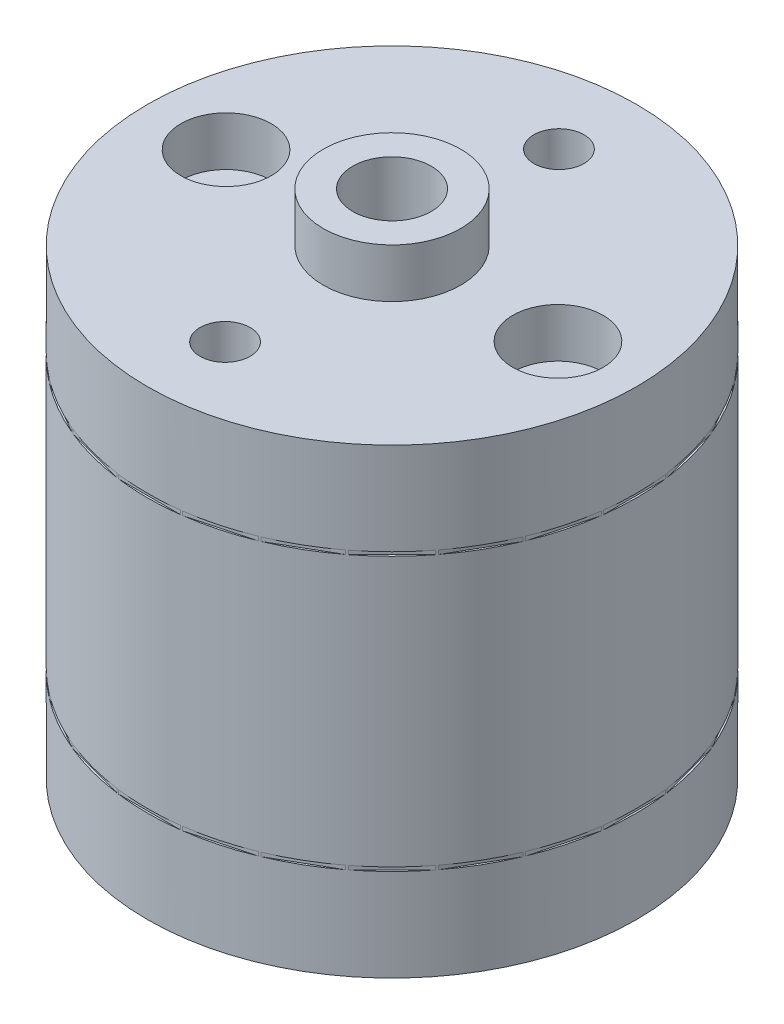
SolidWorks part; units mm, degrees
ref_plane "Alzado" through (0, 0, 0) normal (0, 0, 1) x (1, 0, 0)
ref_plane "Planta" through (0, 0, 0) normal (0, 1, 0) x (1, 0, 0)
ref_plane "Vista lateral" through (0, 0, 0) normal (1, 0, 0) x (0, 0, -1)
sketch "Croquis1" plane through (0, 0, 0) normal (0, 1, 0) x (1, 0, 0)
  circle A0 centre (0, 0) radius 12.45
  dimension "D1" = 24.9
extrude "Saliente-Extruir1" add sketch "Croquis1" along normal blind 23.5
ref_plane "Plano1" through (0, 0, 12.45) normal (0, 0, 1) x (1, 0, 0)
sketch "Croquis2" plane through (0, 0, 12.45) normal (0, 0, 1) x (1, 0, 0)
  line L0 (0, 23.5) -> (0, 0) construction
  line L1 (12.45, 23.5) -> (-12.45, 23.5) construction
  line L2 (-12.45, 23.5) -> (-12.45, 0) construction
  line L3 (-12.45, 18.8) -> (12.45, 18.8)
  line L4 (-12.45, 18.8) -> (-12.45, 18.6)
  line L5 (-12.45, 18.6) -> (12.45, 18.6)
  line L6 (12.45, 18.8) -> (12.45, 18.6)
  line L7 (12.45, 0) -> (12.45, 23.5) construction
  line L8 (-12.45, 0) -> (12.45, 0) construction
  line L9 (-12.45, 4.9) -> (12.45, 4.9)
  line L10 (-12.45, 4.9) -> (-12.45, 4.7)
  line L11 (-12.45, 4.7) -> (12.45, 4.7)
  line L12 (12.45, 4.9) -> (12.45, 4.7)
  point P17 (-12.45, 21.2974)
  dimension "D1" = 4.7
  dimension "D2" = 0.2
  dimension "D3" = 4.7
  dimension "D4" = 0.2
extrude "Cortar-Extruir1" cut sketch "Croquis2" against normal blind 0.1
pattern_circular "MatrizC1" count 24 every 15 about axis through (0, 0, 0) along (0, 1, 0) of "Cortar-Extruir1"
sketch "Croquis5" plane through (0, 23.5, 0) normal (0, 1, 0) x (1, 0, 0)
  circle A0 centre (0, 0) radius 3.5
  dimension "D1" = 7
extrude "Saliente-Extruir2" add sketch "Croquis5" along normal blind 2.5
sketch "Croquis6" plane through (0, 26, 0) normal (0, 1, 0) x (1, 0, 0)
  circle A0 centre (0, 0) radius 2
  dimension "D1" = 4
extrude "Cortar-Extruir3" cut sketch "Croquis6" against normal through all
sketch "Croquis7" plane through (0, 23.5, 0) normal (0, 1, 0) x (1, 0, 0)
  line L0 (0, 12.45) -> (0, -12.45) construction
  line L1 (12.45, 0) -> (-12.45, 0) construction
  circle A0 centre (0, 0) radius 12.45 construction
  circle A1 centre (0, 8.5) radius 1.275
  circle A2 centre (0, -8.5) radius 1.275
  circle A3 centre (-8.45, 0) radius 2.3
  circle A4 centre (8.45, 0) radius 2.3
  point P9 (0, 0)
  point P14 (0, 0)
  dimension "D1" = 2.55
  dimension "D3" = 4.6
  dimension "D2" = 8.5
  dimension "D4" = 8.45
extrude "Cortar-Extruir4" cut sketch "Croquis7" against normal blind 2.5
